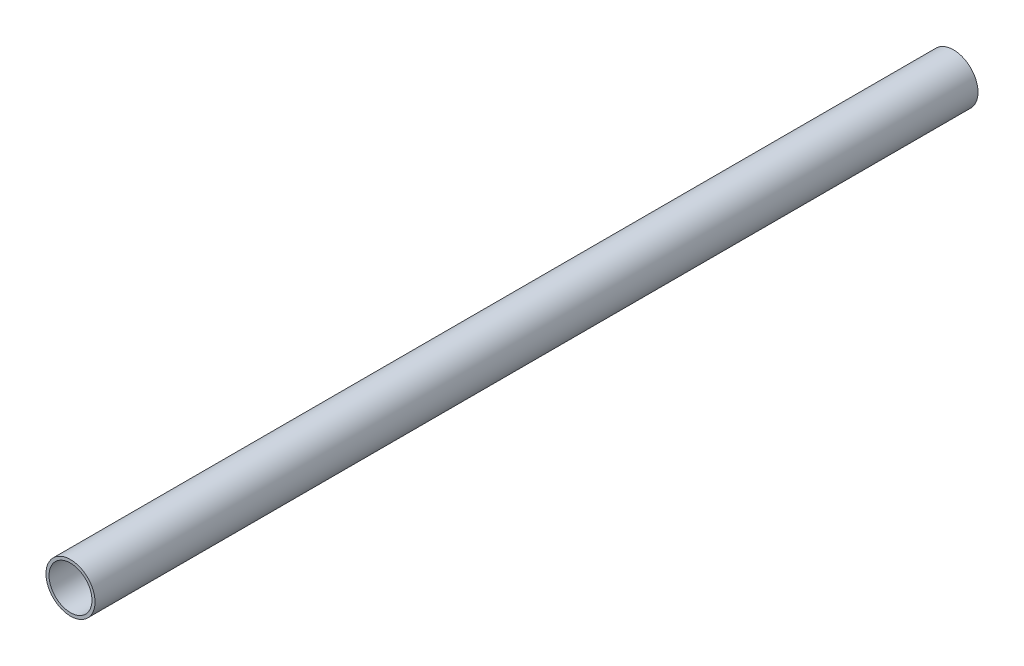
SolidWorks part; units mm, degrees
ref_plane "Front Plane" through (0, 0, 0) normal (0, 0, 1) x (1, 0, 0)
ref_plane "Top Plane" through (0, 0, 0) normal (0, 1, 0) x (1, 0, 0)
ref_plane "Right Plane" through (0, 0, 0) normal (1, 0, 0) x (0, 0, -1)
sketch "Sketch1" plane through (0, 0, 0) normal (0, 0, 1) x (1, 0, 0)
  circle A0 centre (0, 0) radius 12.7
  circle A1 centre (0, 0) radius 11.1125
  dimension "D1" = 22.225
  dimension "D2" = 25.4
extrude "Boss-Extrude1" add sketch "Sketch1" along normal blind 457.2
